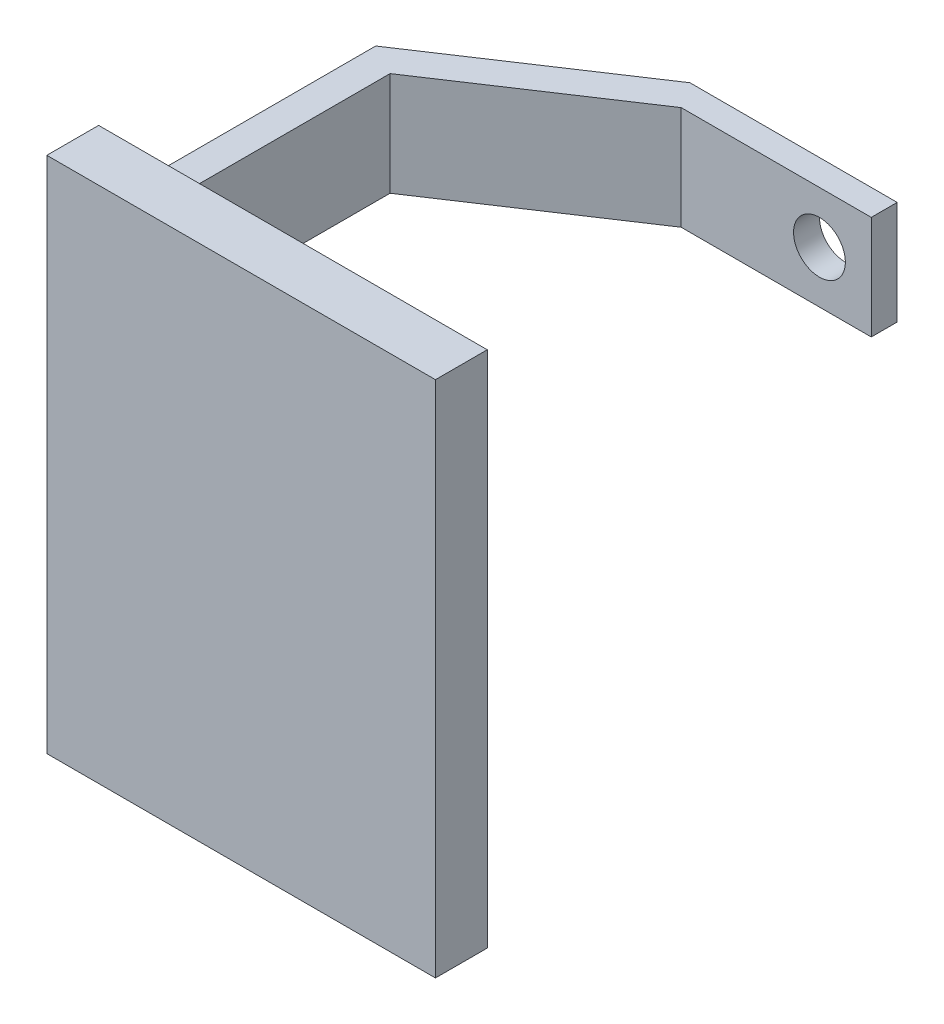
SolidWorks part; units mm, degrees
ref_plane "Front Plane" through (0, 0, 0) normal (0, 0, 1) x (1, 0, 0)
ref_plane "Top Plane" through (0, 0, 0) normal (0, 1, 0) x (1, 0, 0)
ref_plane "Right Plane" through (0, 0, 0) normal (1, 0, 0) x (0, 0, -1)
sketch "Sketch1" plane through (0, 0, 0) normal (0, 0, 1) x (1, 0, 0)
  line L1 (10, 10) -> (-10, 10)
  line L2 (10, 10) -> (10, -10)
  line L3 (10, -10) -> (-10, -10)
  line L4 (-10, 10) -> (-10, -10)
  line L5 (10, 10) -> (-10, -10) construction
  line L6 (10, -10) -> (-10, 10) construction
  circle A0 centre (0, 0) radius 5
  dimension "D1" = 10
  dimension "D2" = 20
  dimension "D3" = 20
extrude "Boss-Extrude1" add sketch "Sketch1" along normal blind 5
sketch "Sketch2" plane through (-10, 0, 0) normal (-1, 0, 0) x (0, 0, 1)
  line L4 (0, 10) -> (0, -10)
  line L5 (0, -10) -> (5, -10)
  line L6 (5, -10) -> (5, 10)
  line L7 (5, 10) -> (0, 10)
  line L8 (0, 10) -> (0, -10)
  line L9 (0, -10) -> (5, -10)
  line L10 (5, -10) -> (5, 10)
  line L11 (5, 10) -> (0, 10)
  dimension "D1" = 0
extrude "Boss-Extrude2" add sketch "Sketch2" along normal blind 20
sketch "Sketch8" plane through (0, -10, 0) normal (0, -1, 0) x (1, 0, 0)
  line L0 (-30, 0) -> (-26.6834, 5)
  line L1 (-30, 0) -> (-66.4576, 24.1832)
  line L2 (-26.6834, 5) -> (-63.141, 29.1832)
  line L3 (-66.4576, 24.1832) -> (-63.141, 29.1832)
  line L4 (-30, 5) -> (10, 5) construction
  line L5 (-66.4576, 24.1832) -> (-60.4576, 24.1832)
  line L6 (-66.4576, 24.1832) -> (-66.4576, 74.1832)
  line L7 (-60.4576, 24.1832) -> (-60.4576, 74.1832)
  line L8 (-66.4576, 74.1832) -> (-60.4576, 74.1832)
  line L9 (-66.4576, 74.1832) -> (-61.4576, 70.8666)
  line L10 (-66.4576, 74.1832) -> (-39.9246, 114.1832)
  line L11 (-61.4576, 70.8666) -> (-34.9246, 110.8666)
  line L12 (-39.9246, 114.1832) -> (-34.9246, 110.8666)
  line L13 (-39.9246, 114.1832) -> (-39.9246, 104.1832)
  line L14 (-39.9246, 114.1832) -> (35.0754, 114.1832)
  line L15 (-39.9246, 104.1832) -> (35.0754, 104.1832)
  line L16 (35.0754, 114.1832) -> (35.0754, 104.1832)
  point P7 (-40.547, 17.2763)
  point P15 (-48.5428, 19.1676)
  point P18 (-27.642, 5.069)
  point P19 (-30, 0)
  point P20 (-44.2059, 16.6232)
  point P21 (-36.2613, 85.5732)
  point P22 (0, 0)
  point P23 (0, 0)
  point P24 (-39.9246, 114.1832)
  line M14 (10, 5) -> (-30, 5)
  line M15 (-30, 5) -> (-30, 0)
  dimension "D1" = 6
  dimension "D2" = 6
  dimension "D3" = 75
  dimension "D4" = 6
  dimension "D5" = 10
  dimension "D6" = 50
  dimension "D7" = 40
extrude "Boss-Extrude6" add sketch "Sketch8" against normal up to surface (20 mm away) contours L16 L14 L12 L11 L15 | L13 L15 L11 L12 | L15 L13 L10 L8 L7 L11 | L9 L11 L7 L8 | L11 L9 L6 L3 L2 L7 | L5 L7 L2 L3 | L7 L5 L1 L2 M15 M14 up to face at (-10, 10, 2.5)
sketch "Sketch9" plane through (0, -10, 0) normal (0, -1, 0) x (1, 0, 0)
  line L1 (35.0754, 104.1832) -> (-39.9246, 104.1832)
  line L2 (35.0754, 104.1832) -> (35.0754, 114.1832)
  line L3 (35.0754, 114.1832) -> (-39.9246, 114.1832)
  line L4 (-39.9246, 104.1832) -> (-39.9246, 114.1832)
extrude "Boss-Extrude7" add sketch "Sketch9" along normal blind 40 and the other way blind 60
